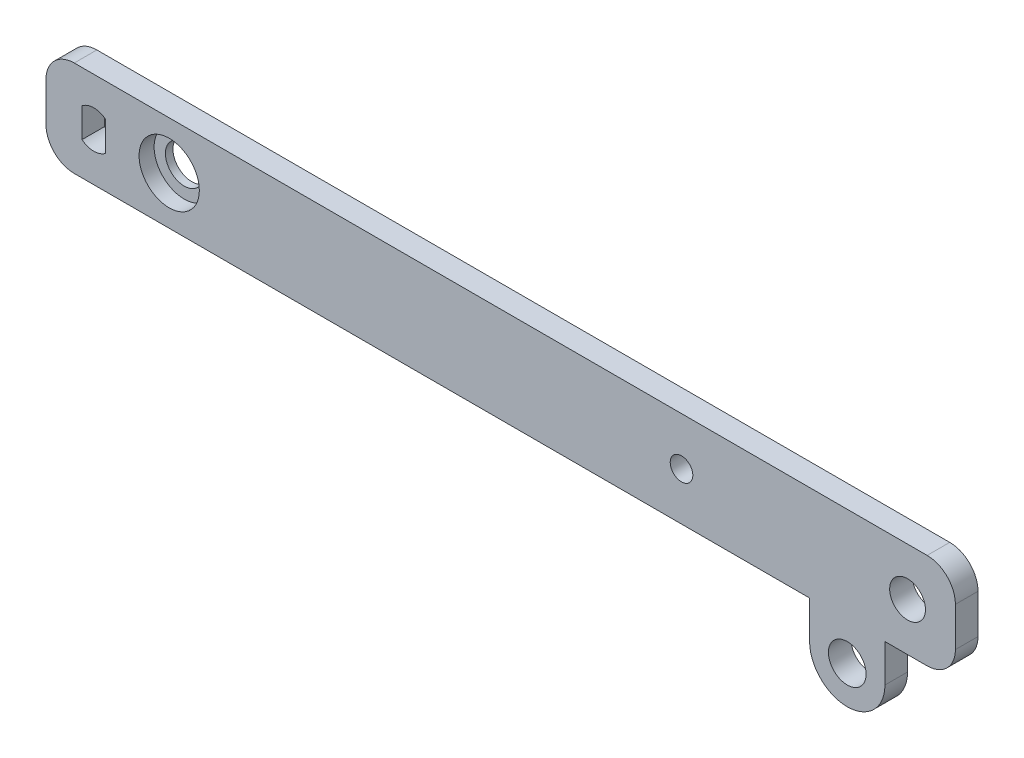
SolidWorks part; units mm, degrees
ref_plane "Alzado" through (0, 0, 0) normal (0, 0, 1) x (1, 0, 0)
ref_plane "Planta" through (0, 0, 0) normal (0, 1, 0) x (1, 0, 0)
ref_plane "Vista lateral" through (0, 0, 0) normal (1, 0, 0) x (0, 0, -1)
sketch "Croquis1" plane through (0, 0, 0) normal (0, 0, 1) x (1, 0, 0)
  line L0 (0, 0) -> (432, 0) construction
  line L1 (380, -45.4) -> (380, -25.4)
  line L2 (-6.28, -7.7821) -> (-6.28, 7.7821)
  line L3 (-25.4, 25.4) -> (457.4, 25.4)
  line L4 (6.28, -7.7821) -> (6.28, 7.7821)
  line L5 (-6.28, -7.7821) -> (6.28, 7.7821) construction
  line L6 (-6.28, 7.7821) -> (6.28, -7.7821) construction
  line L7 (-25.4, 25.4) -> (-25.4, -25.4)
  line L8 (-25.4, -25.4) -> (380, -25.4)
  line L9 (457.4, 25.4) -> (457.4, -25.4)
  line L10 (420, -45.4) -> (420, -25.4)
  line L11 (420, -25.4) -> (457.4, -25.4)
  arc A0 (-6.28, -7.7821) -> (6.28, -7.7821) centre (0, 0) ccw
  arc A1 (6.28, 7.7821) -> (-6.28, 7.7821) centre (0, 0) ccw
  circle A2 centre (432, 0) radius 9.5
  circle A3 centre (40, 0) radius 10
  circle A4 centre (312, 0) radius 6
  circle A5 centre (400, -45.4) radius 10
  arc A6 (380, -45.4) -> (420, -45.4) centre (400, -45.4) ccw
  dimension "D1" = 20
  dimension "D4" = 19
  dimension "D5" = 20
  dimension "D6" = 40
  dimension "D9" = 25.4
  dimension "D10" = 25.4
  dimension "D11" = 12
  dimension "D12" = 120
  dimension "D13" = 20
  dimension "D14" = 20
  dimension "D15" = 20
  dimension "D16" = 360
  dimension "D2" = 12.56
  dimension "D3" = 432
  dimension "D7" = 50.8
  dimension "D8" = 25.4
extrude "Saliente-Extruir1" add sketch "Croquis1" along normal blind 12
sketch "Croquis2" plane through (0, 0, 0) normal (0, 0, -1) x (-1, 0, 0)
  circle A0 centre (-66.437, -11.2982) radius 2.145
extrude "Cortar-Extruir1" cut sketch "Croquis2" against normal blind 3
sketch "Croquis3" plane through (0, 0, 0) normal (0, 0, -1) x (-1, 0, 0)
  circle A0 centre (-40, 0) radius 16
  dimension "D1" = 32
fillet "Redondeo1" radius 15 2 edges at (-25.4, -25.4, 6) (-25.4, 25.4, 6)
fillet "Redondeo2" radius 15 2 edges at (457.4, -25.4, 6) (457.4, 25.4, 6)
sketch "Croquis4" plane through (0, 0, 12) normal (0, 0, 1) x (1, 0, 0)
  circle A0 centre (40, 0) radius 16
  dimension "D1" = 32
extrude "Cortar-Extruir2" cut sketch "Croquis4" against normal blind 8
